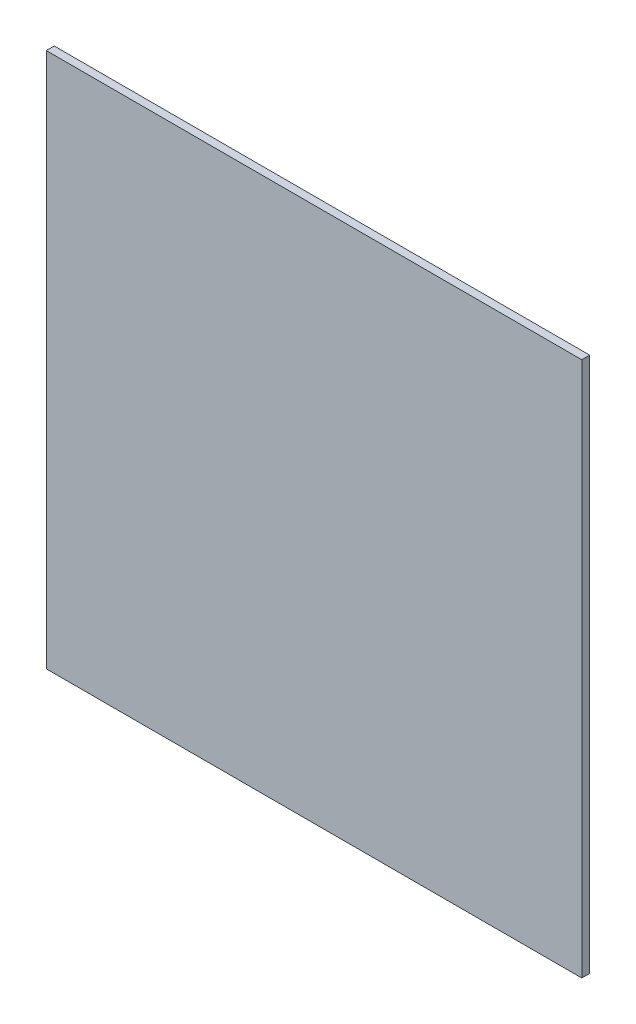
SolidWorks part; units mm, degrees
ref_plane "Front Plane" through (0, 0, 0) normal (0, 0, 1) x (1, 0, 0)
ref_plane "Top Plane" through (0, 0, 0) normal (0, 1, 0) x (1, 0, 0)
ref_plane "Right Plane" through (0, 0, 0) normal (1, 0, 0) x (0, 0, -1)
sketch "Sketch1" plane through (0, 0, 0) normal (0, 0, 1) x (1, 0, 0)
  line L1 (0, 0) -> (27, 0)
  line L2 (0, 0) -> (0, 27)
  line L3 (0, 27) -> (27, 27)
  line L4 (27, 0) -> (27, 27)
  dimension "D1" = 27
extrude "Profile" add sketch "Sketch1" along normal blind 0.4
equation "\"Profile_Depth\"= 0.4mm"
equation "\"D1@Profile\" = \"Profile_Depth\""
equation "\"Profile_Sketch_1\"= 27mm"
equation "\"D1@Sketch1\" = \"Profile_Sketch_1\""
equation "\"EnvelopeWidth\"= 27mm"
equation "\"EnvelopeHeight\"= 27mm"
